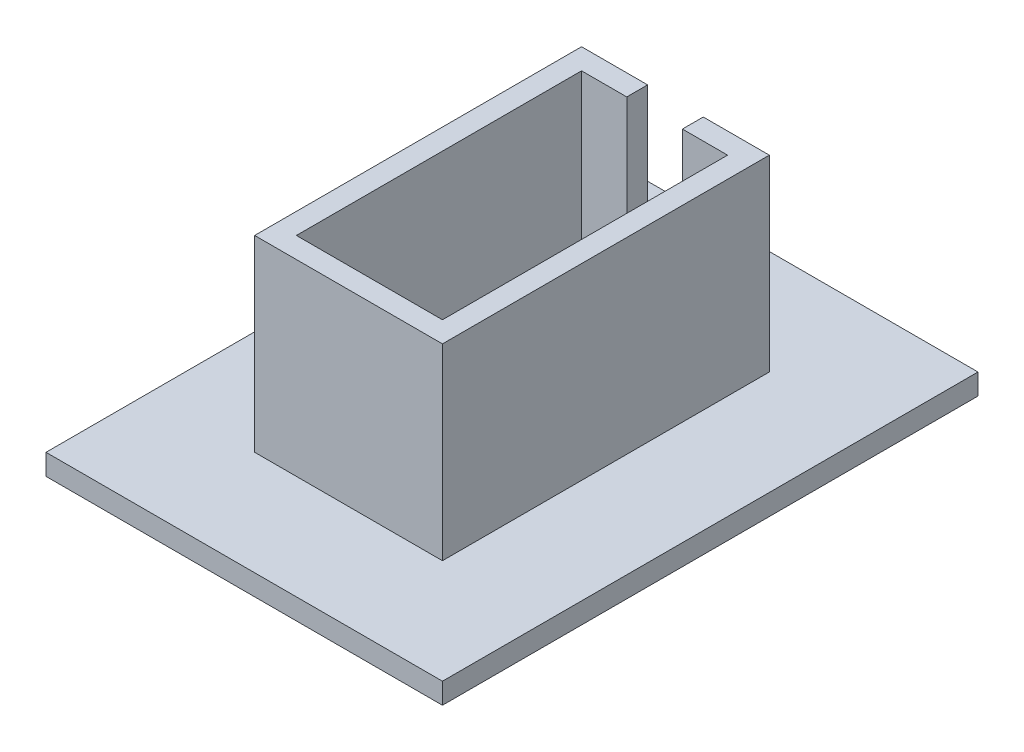
SolidWorks part; units mm, degrees
ref_plane "Front Plane" through (0, 0, 0) normal (0, 0, 1) x (1, 0, 0)
ref_plane "Top Plane" through (0, 0, 0) normal (0, 1, 0) x (1, 0, 0)
ref_plane "Right Plane" through (0, 0, 0) normal (1, 0, 0) x (0, 0, -1)
sketch "Sketch2" plane through (0, 0, 0) normal (0, 1, 0) x (1, 0, 0)
  line L1 (-63.3817, 75.6678) -> (-6.3817, 75.6678)
  line L2 (-63.3817, 75.6678) -> (-63.3817, -1.3322)
  line L3 (-63.3817, -1.3322) -> (-6.3817, -1.3322)
  line L4 (-6.3817, 75.6678) -> (-6.3817, -1.3322)
  dimension "D1" = 57
  dimension "D2" = 77
extrude "Boss-Extrude1" add sketch "Sketch2" along normal blind 3 contours L2 L1 L4 L3
sketch "Sketch3" plane through (0, 3, 0) normal (0, 1, 0) x (1, 0, 0)
  line L0 (-63.3817, 37.1678) -> (-48.3817, 37.1678) construction
  line L1 (-48.3817, 60.6678) -> (-21.3817, 60.6678)
  line L2 (-48.3817, 60.6678) -> (-48.3817, 13.6678)
  line L3 (-48.3817, 13.6678) -> (-21.3817, 13.6678)
  line L4 (-21.3817, 60.6678) -> (-21.3817, 13.6678)
  line L6 (-63.3817, 75.6678) -> (-63.3817, -1.3322) construction
  line L7 (-34.8817, 60.6678) -> (-34.8817, 75.6678) construction
  line L8 (-63.3817, 75.6678) -> (-6.3817, 75.6678) construction
  line L9 (-45.3817, 37.1678) -> (-48.3817, 37.1678) construction
  line L10 (-45.3817, 16.6678) -> (-24.3817, 16.6678)
  line L11 (-45.3817, 16.6678) -> (-45.3817, 57.6678)
  line L12 (-45.3817, 57.6678) -> (-24.3817, 57.6678)
  line L13 (-24.3817, 16.6678) -> (-24.3817, 57.6678)
  line L14 (-34.8817, 57.6678) -> (-34.8817, 60.6678) construction
  dimension "D1" = 27
  dimension "D2" = 47
  dimension "D3" = 41
  dimension "D4" = 21
extrude "Boss-Extrude2" add sketch "Sketch3" along normal blind 27
sketch "Sketch5" plane through (0, 30, 0) normal (0, 1, 0) x (1, 0, 0)
  line L0 (-24.3817, 57.6678) -> (-45.3817, 57.6678) construction
  line L1 (-30.8817, 57.6678) -> (-38.8817, 57.6678)
  line L2 (-30.8817, 57.6678) -> (-30.8817, 60.6678)
  line L3 (-30.8817, 60.6678) -> (-38.8817, 60.6678)
  line L4 (-38.8817, 57.6678) -> (-38.8817, 60.6678)
  line L5 (-21.3817, 60.6678) -> (-48.3817, 60.6678) construction
  line L6 (-38.8817, 59.1678) -> (-48.3817, 59.1678) construction
  line L8 (-30.8817, 59.1678) -> (-21.3817, 59.1678) construction
  line L9 (-21.3817, 13.6678) -> (-21.3817, 60.6678) construction
  line L10 (-48.3817, 60.6678) -> (-48.3817, 13.6678) construction
  line L11 (-38.8817, 59.1678) -> (-30.8817, 59.1678) construction
  dimension "D1" = 8
extrude "Cut-Extrude1" cut sketch "Sketch5" against normal blind 27 contours L3 L4 L1 L2
